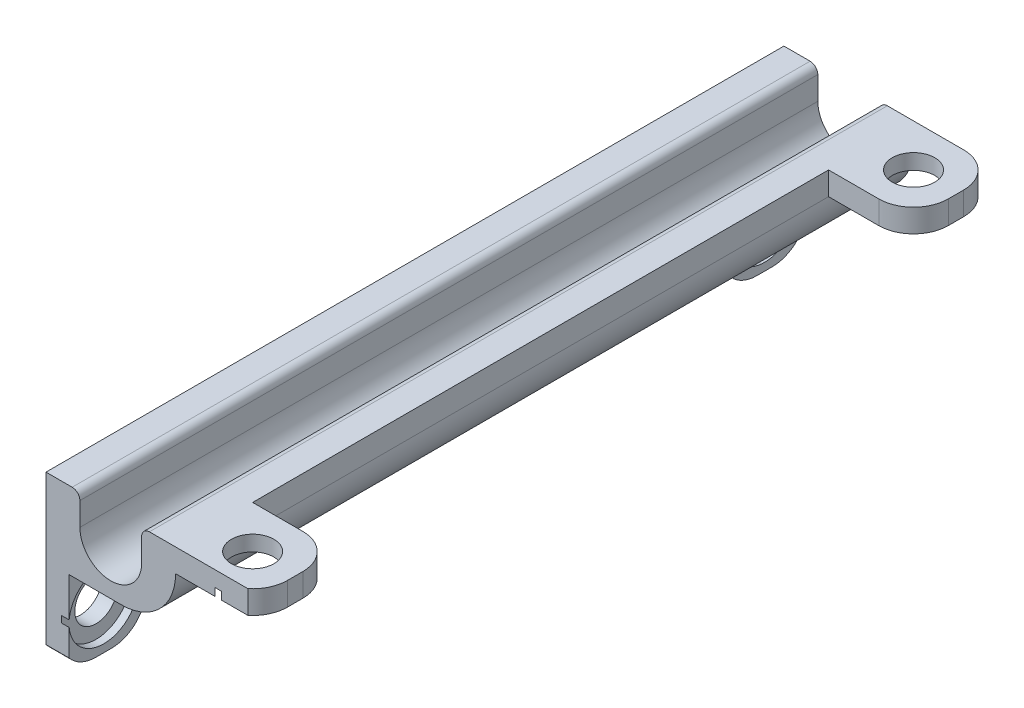
SolidWorks part; units mm, degrees
ref_plane "Front Plane" through (0, 0, 0) normal (0, 0, 1) x (1, 0, 0)
ref_plane "Top Plane" through (0, 0, 0) normal (0, 1, 0) x (1, 0, 0)
ref_plane "Right Plane" through (0, 0, 0) normal (1, 0, 0) x (0, 0, -1)
sketch "Sketch1" plane through (0, 14.9149, 0) normal (0, -1, 0) x (1, 0, 0)
  line L1 (-3.6421, 36.9499) -> (4.7489, 36.9499)
  line L2 (-3.6421, 36.9499) -> (-3.6421, -11.3443)
  line L3 (-3.6421, -11.3443) -> (4.7489, -11.3443)
  line L4 (4.7489, 36.9499) -> (4.7489, -11.3443)
  line L8 (-3.6421, 34.3499) -> (4.7489, 34.3499)
  line L10 (-3.6421, 34.3499) -> (4.7489, 34.3499)
  line L12 (4.7489, 34.3499) -> (4.7489, 21.3499)
  line L14 (4.7489, 34.3499) -> (4.7489, 21.3499)
  line L384 (4.7489, 21.3499) -> (-3.6421, 21.3499)
  line L385 (4.7489, 21.3499) -> (-3.6421, 21.3499)
  line L386 (-3.6421, 21.3499) -> (-3.6421, -31.3443)
  line L387 (-3.6421, 21.3499) -> (-3.6421, -31.3443)
  line L388 (-3.6421, -31.3443) -> (53.3579, -31.3443)
  line L389 (-3.6421, -31.3443) -> (53.3579, -31.3443)
  line L390 (53.3579, -31.3443) -> (53.3579, 36.9499)
  line L391 (53.3579, -31.3443) -> (53.3579, 36.9499)
  line L392 (53.3579, 36.9499) -> (-3.6421, 36.9499)
  line L393 (53.3579, 36.9499) -> (-3.6421, 36.9499)
  line L394 (-3.6421, 36.9499) -> (-3.6421, 34.3499)
  line L395 (-3.6421, 36.9499) -> (-3.6421, 34.3499)
  line M19 (-3.6421, 34.3499) -> (4.7489, 34.3499)
  line M20 (4.7489, 34.3499) -> (4.7489, 21.3499)
  line M21 (4.7489, 21.3499) -> (-3.6421, 21.3499)
  line M22 (-3.6421, 21.3499) -> (-3.6421, -31.3443)
  line M25 (53.3579, 36.9499) -> (-3.6421, 36.9499)
  line M26 (-3.6421, 36.9499) -> (-3.6421, 34.3499)
  dimension "D1" = 0
extrude "Boss-Extrude1" add sketch "Sketch1" along normal blind 5 contours L4 L3 M21 M22 | L2 M19 M21 M20 | L4 M25 M26 M19
sketch "Sketch2" plane through (0, 0, -11.3443) normal (0, 0, -1) x (-1, 0, 0)
  line L0 (-2.5534, 12.9149) -> (-2.5534, 14.9149)
  line L1 (1.4466, 12.9149) -> (1.4466, 14.9149)
  line L2 (-2.5534, 14.9149) -> (1.4466, 14.9149)
  line L4 (3.6421, 14.9149) -> (-4.7489, 14.9149)
  line L5 (-4.7489, 14.9149) -> (-4.7489, 9.9149)
  line L6 (3.6421, 14.9149) -> (-4.7489, 14.9149) construction
  line L7 (3.6421, 9.9149) -> (3.6421, 14.9149)
  line L9 (-4.7489, 14.9149) -> (-4.7489, 9.9149) construction
  line L11 (3.6421, 9.9149) -> (3.6421, 14.9149) construction
  line L14 (-4.7489, 9.9149) -> (3.6421, 9.9149)
  line L15 (-4.7489, 9.9149) -> (3.6421, 9.9149) construction
  arc A0 (-2.5534, 12.9149) -> (1.4466, 12.9149) centre (-0.5534, 12.9149) ccw
  point P4 (-0.5534, 14.9149)
  dimension "D2" = 4
  dimension "D3" = 2
extrude "Cut-Extrude1" cut sketch "Sketch2" against normal through all and the other way through all
sketch "Sketch3" plane through (0, 14.9149, 0) normal (0, 1, 0) x (1, 0, 0)
  line L0 (-3.6421, -36.9499) -> (-3.6421, 11.3443) construction
  line L1 (4.7489, 11.3443) -> (4.7489, -36.9499)
  line L2 (4.7489, -12.8028) -> (-3.6421, -12.8028) construction
  line L3 (4.7489, 11.3443) -> (10.2489, 11.3443)
  line L4 (4.7489, 11.3443) -> (4.7489, 5.8443)
  line L5 (4.7489, 5.8443) -> (10.2489, 5.8443)
  line L6 (10.2489, 11.3443) -> (10.2489, 5.8443)
  line L8 (10.2489, -36.9499) -> (10.2489, -31.4499)
  line L9 (4.7489, -31.4499) -> (10.2489, -31.4499)
  line L10 (4.7489, -36.9499) -> (4.7489, -31.4499)
  line L11 (4.7489, -36.9499) -> (10.2489, -36.9499)
  line L13 (4.7489, -36.9499) -> (4.7489, 11.3443) construction
  line L14 (4.7489, -36.9499) -> (4.7489, 11.3443)
  circle A0 centre (7.4989, 8.5943) radius 1.375
  circle A1 centre (7.4989, -34.1999) radius 1.375
  point P7 (7.4989, 11.3443)
  point P8 (10.2489, 8.5943)
  dimension "D3" = 2.75
  dimension "D1" = 5.5
  dimension "D2" = 5.5
extrude "Extrude Bottom Screw Pads" add sketch "Sketch3" against normal blind 1.5
sketch "Sketch4" plane through (0, 13.4149, 0) normal (0, -1, 0) x (1, 0, 0)
  circle A0 centre (7.4989, -8.5943) radius 1.375 construction
  circle A1 centre (7.4989, 34.1999) radius 1.375 construction
  circle A2 centre (7.4989, -8.5943) radius 1.375 construction
  circle A3 centre (7.4989, 34.1999) radius 1.375 construction
  circle A4 centre (7.4989, 34.1999) radius 2.25
  circle A5 centre (7.4989, -8.5943) radius 2.25
  dimension "D1" = 4.5
  dimension "D2" = 4.5
extrude "Cut Bottom Countersink" cut sketch "Sketch4" against normal blind 0.5
sketch "Sketch5" plane through (-3.6421, 0, 0) normal (-1, 0, 0) x (0, 0, 1)
  line L0 (36.9499, 9.9149) -> (36.9499, 14.9149) construction
  line L1 (36.9499, 9.9149) -> (-11.3443, 9.9149) construction
  line L2 (12.8028, 9.9149) -> (12.8028, 14.9149) construction
  line L3 (36.9499, 9.9149) -> (31.4499, 9.9149)
  line L4 (36.9499, 9.9149) -> (36.9499, 4.4149)
  line L5 (36.9499, 4.4149) -> (31.4499, 4.4149)
  line L6 (31.4499, 9.9149) -> (31.4499, 4.4149)
  line L8 (-5.8443, 9.9149) -> (-5.8443, 4.4149)
  line L9 (-11.3443, 4.4149) -> (-5.8443, 4.4149)
  line L10 (-11.3443, 9.9149) -> (-11.3443, 4.4149)
  line L11 (-11.3443, 9.9149) -> (-5.8443, 9.9149)
  line L12 (36.9499, 14.9149) -> (-11.3443, 14.9149) construction
  line L13 (36.9499, 9.9149) -> (-11.3443, 9.9149) construction
  circle A0 centre (34.1999, 7.1649) radius 1.375
  circle A1 centre (-8.5943, 7.1649) radius 1.375
  point P7 (34.1999, 4.4149)
  point P8 (36.9499, 7.1649)
  dimension "D3" = 2.75
  dimension "D1" = 5.5
  dimension "D2" = 5.5
extrude "Extrude Side Screw Pads" add sketch "Sketch5" against normal blind 1.5
sketch "Sketch6" plane through (-2.1421, 0, 0) normal (1, 0, 0) x (0, 0, -1)
  circle A0 centre (-34.1999, 7.1649) radius 1.375 construction
  circle A1 centre (8.5943, 7.1649) radius 1.375 construction
  circle A2 centre (-34.1999, 7.1649) radius 1.375 construction
  circle A3 centre (8.5943, 7.1649) radius 1.375 construction
  circle A4 centre (-34.1999, 7.1649) radius 2.25
  circle A5 centre (8.5943, 7.1649) radius 2.25
  dimension "D1" = 4.5
  dimension "D2" = 4.5
extrude "Cut Side Countersink" cut sketch "Sketch6" against normal blind 0.5
fillet "Fillet Screw Pads" radius 2.25 8 edges at (10.2489, 14.1649, -5.8443) (10.2489, 14.1649, -11.3443) (-2.8921, 4.4149, -5.8443) (-2.8921, 4.4149, -11.3443) (-2.8921, 4.4149, 36.9499) (-2.8921, 4.4149, 31.4499) (10.2489, 14.1649, 31.4499) (10.2489, 14.1649, 36.9499)
fillet "Fillet4" radius 3.5 1 edges at (4.7489, 9.9149, 12.8028)
fillet "Fillet5" radius 0.5 2 edges at (-1.4466, 14.9149, 12.8028) (2.5534, 14.9149, 12.8028)
sketch "Sketch7" plane through (0, 0, 36.9499) normal (0, 0, 1) x (1, 0, 0)
  line L0 (-2.1421, 4.4149) -> (-3.6421, 4.4149) construction
  line L1 (-3.6421, 14.9149) -> (10.2489, 14.9149)
  line L2 (-3.6421, 14.9149) -> (-3.6421, 4.4149)
  line L3 (-3.6421, 4.4149) -> (10.2489, 4.4149)
  line L4 (10.2489, 14.9149) -> (10.2489, 4.4149)
  line L5 (10.2489, 14.9149) -> (10.2489, 13.4149) construction
extrude "Cut-Extrude4" cut sketch "Sketch7" against normal blind 0.51
equation "\"cable diameter\" = 4"
equation "\"tolerance\"= 0.5"
equation "\"thru hole diameter\"= 2.75"
equation "\"screw cap diameter\"= 4.5"
equation "\"screw cap countersink\"= 0.5"
equation "\"distance to wall\"=20"
equation "\"D1@Boss-Extrude1\" = \"cable cover height\""
equation "\"D2@Sketch2\"=\"cable diameter\""
equation "\"cable cover height\"= 5"
equation "\"D1@Sketch3\"=\"screw cap diameter\"+\"tolerance\"*2"
equation "\"D2@Sketch3\"=\"D1@Sketch3\""
equation "\"D3@Sketch3\"=\"thru hole diameter\""
equation "\"screw pad depth\"= 1.5"
equation "\"D1@Extrude Bottom Screw Pads\" = \"screw pad depth\""
equation "\"D1@Sketch4\"=\"screw cap diameter\""
equation "\"D2@Sketch4\"=\"screw cap diameter\""
equation "\"D1@Sketch5\"=\"screw cap diameter\"+\"tolerance\"*2"
equation "\"D2@Sketch5\"=\"screw cap diameter\"+\"tolerance\"*2"
equation "\"D3@Sketch5\"=\"thru hole diameter\""
equation "\"D1@Extrude Side Screw Pads\" = \"screw pad depth\""
equation "\"D1@Sketch6\"=\"screw cap diameter\""
equation "\"D2@Sketch6\"=\"screw cap diameter\""
equation "\"cable cover fillet\"= \"cable cover height\" - \"screw pad depth\""
equation "\"D1@Cut Side Countersink\"=\"screw cap countersink\""
equation "\"D3@Sketch2\"=\"cable diameter\"/2"
equation "\"D1@Fillet4\"=\"cable cover fillet\""
equation "\"D1@Fillet5\"=\"tolerance\""
equation "\"D1@Cut-Extrude3\" = \"tolerance\" + 0.01"
